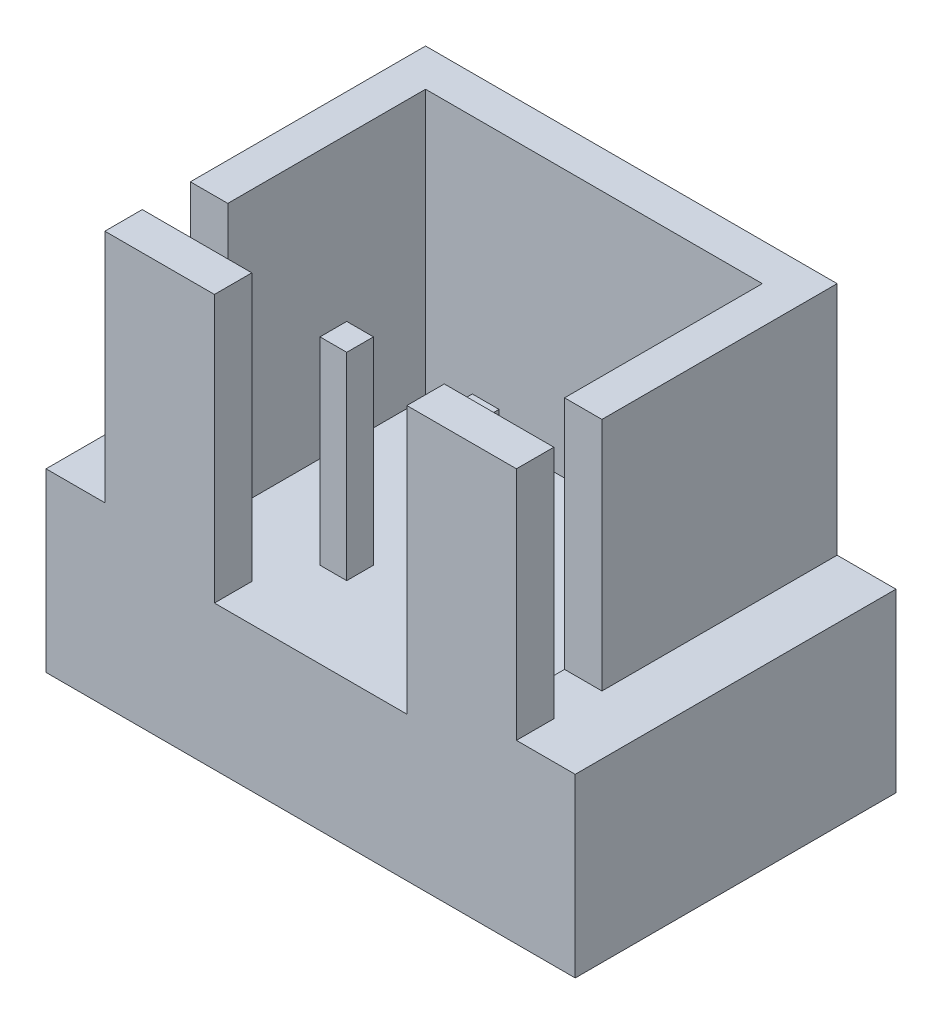
SolidWorks part; units mm, degrees
ref_plane "Front" through (0, 0, 0) normal (0, 0, 1) x (1, 0, 0)
ref_plane "Top" through (0, 0, 0) normal (0, 1, 0) x (1, 0, 0)
ref_plane "Right" through (0, 0, 0) normal (1, 0, 0) x (0, 0, -1)
sketch "Sketch1" plane through (0, 0, 0) normal (0, 1, 0) x (1, 0, 0)
  line L0 (0, 3) -> (0, 0) construction
  line L1 (-4.95, 3) -> (4.95, 3)
  line L2 (-4.95, 3) -> (-4.95, -3)
  line L3 (-4.95, -3) -> (4.95, -3)
  line L4 (4.95, 3) -> (4.95, -3)
  line L5 (0, 0) -> (4.95, 0) construction
  dimension "D1" = 9.9
  dimension "D2" = 6
extrude "Boss-Extrude1" add sketch "Sketch1" along normal blind 7.7
sketch "Sketch2" plane through (0, 7.7, 0) normal (0, 1, 0) x (1, 0, 0)
  line L1 (-3.15, 2.3) -> (3.15, 2.3)
  line L2 (-3.15, 2.3) -> (-3.15, -2.3)
  line L3 (-3.15, -2.3) -> (3.15, -2.3)
  line L4 (3.15, 2.3) -> (3.15, -2.3)
  line L5 (0, 3) -> (0, 0) construction
  line L6 (0, 0) -> (4.118, 0) construction
  line L7 (0, 0) -> (4.95, 0) construction
  dimension "D1" = 6.3
  dimension "D2" = 4.6
extrude "Cut-Extrude1" cut sketch "Sketch2" against normal blind 5
sketch "Sketch3" plane through (0, 7.7, 0) normal (0, 1, 0) x (1, 0, 0)
  line L0 (-4.95, -3) -> (4.95, -3) construction
  line L1 (-4.95, 3) -> (-3.85, 3)
  line L2 (-4.95, 3) -> (-4.95, -3)
  line L3 (-4.95, -3) -> (-3.85, -3)
  line L4 (-3.85, 3) -> (-3.85, -3)
  line L6 (4.95, 3) -> (3.85, 3)
  line L7 (4.95, 3) -> (4.95, -3)
  line L8 (4.95, -3) -> (3.85, -3)
  line L9 (3.85, 3) -> (3.85, -3)
  dimension "D1" = 1.1
extrude "Cut-Extrude2" cut sketch "Sketch3" against normal blind 4.4
sketch "Sketch4" plane through (0, 7.7, 0) normal (0, 1, 0) x (1, 0, 0)
  line L0 (0, 0) -> (0, -3) construction
  line L1 (-4.95, -3) -> (4.95, -3) construction
  line L2 (-3.15, -2.3) -> (3.15, -2.3) construction
  line L3 (-1.8, -2.3) -> (1.8, -2.3)
  line L4 (-1.8, -2.3) -> (-1.8, -3)
  line L5 (-1.8, -3) -> (1.8, -3)
  line L10 (1.8, -2.3) -> (1.8, -3)
  dimension "D1" = 3.6
extrude "Cut-Extrude3" cut sketch "Sketch4" against normal up to surface (5 mm away) up to face at (0, 2.7, 0)
sketch "Sketch5" plane through (0, 7.7, 0) normal (0, 1, 0) x (1, 0, 0)
  line L0 (-3.85, -3) -> (-3.85, 3) construction
  line L1 (-3.85, -1.4) -> (3.85, -1.4)
  line L2 (-3.85, -1.4) -> (-3.85, -2.3)
  line L3 (-3.85, -2.3) -> (3.85, -2.3)
  line L4 (3.85, -1.4) -> (3.85, -2.3)
  line L5 (3.85, 3) -> (3.85, -3) construction
  line L6 (1.8, -2.3) -> (3.15, -2.3) construction
  dimension "D1" = 0.9
extrude "Cut-Extrude4" cut sketch "Sketch5" against normal up to surface (4.4 mm away) up to face at (4.4, 3.3, 0)
sketch "Sketch6" plane through (0, 2.7, 0) normal (0, 1, 0) x (1, 0, 0)
  line L0 (-3.85, -1.4) -> (3.85, -1.4) construction
  line L5 (0, 0) -> (0, 4.0905) construction
  line L6 (-1.425, -0.9) -> (-0.925, -0.9)
  line L7 (-1.425, -0.9) -> (-1.425, -1.4)
  line L8 (-1.425, -1.4) -> (-0.925, -1.4)
  line L9 (-0.925, -0.9) -> (-0.925, -1.4)
  line L10 (0.925, -0.9) -> (0.925, -1.4)
  line L11 (1.425, -1.4) -> (0.925, -1.4)
  line L12 (1.425, -0.9) -> (1.425, -1.4)
  line L13 (1.425, -0.9) -> (0.925, -0.9)
  dimension "D1" = 1.85
  dimension "D2" = 0.5
extrude "Boss-Extrude2" add sketch "Sketch6" along normal blind 3.7
